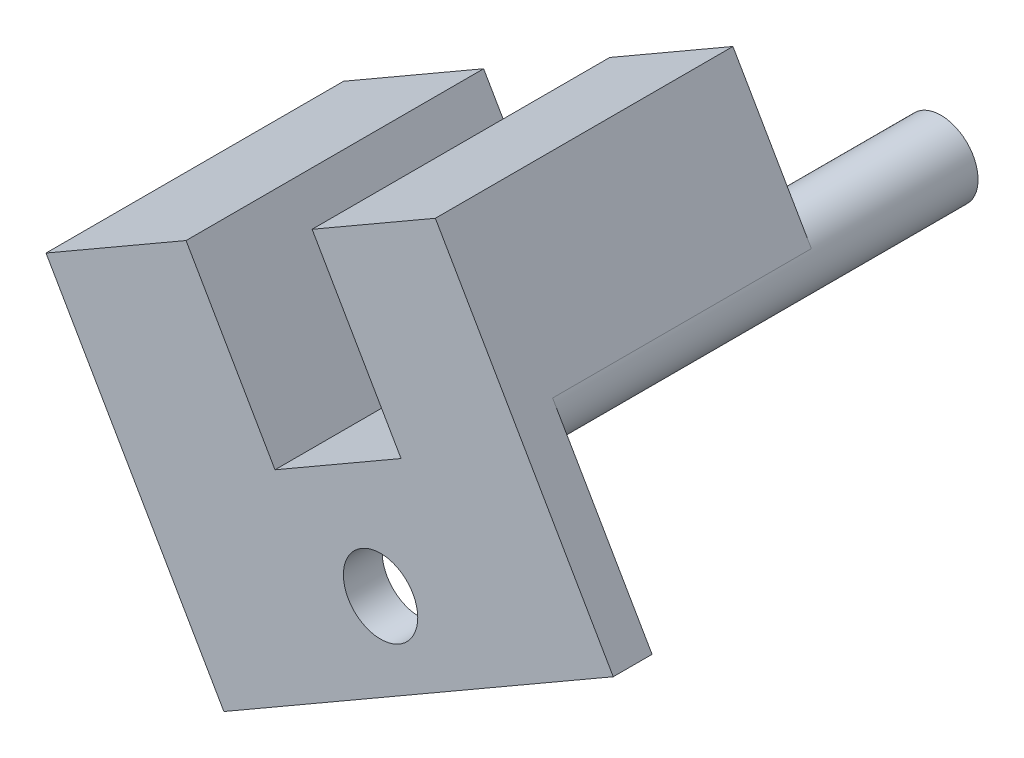
SolidWorks part; units mm, degrees
material "ABS"
ref_plane "Plan de face" through (0, 0, 0) normal (0, 0, 1) x (1, 0, 0)
ref_plane "Plan de dessus" through (0, 0, 0) normal (0, 1, 0) x (1, 0, 0)
ref_plane "Plan de droite" through (0, 0, 0) normal (1, 0, 0) x (0, 0, -1)
sketch "Esquisse1" plane through (0, 0, 0) normal (0, 0, 1) x (1, 0, 0)
  line L0 (-14.7601, -47.6561) -> (-4.7142, -41.8561)
  line L1 (-4.2932, -40.2851) -> (-6.7182, -36.0849)
  line L2 (-6.7182, -36.0849) -> (-10.5288, -38.2849)
  line L3 (-10.5288, -38.2849) -> (-7.7788, -43.0481)
  line L4 (-7.7788, -43.0481) -> (-11.6759, -45.2981)
  line L5 (-11.6759, -45.2981) -> (-14.4259, -40.5349)
  line L6 (-14.4259, -40.5349) -> (-18.756, -43.0349)
  line L7 (-18.756, -43.0349) -> (-16.331, -47.2351)
  circle A0 centre (-5.2892, -40.8601) radius 1.15 construction
  circle A1 centre (-15.3351, -46.6601) radius 1.15 construction
  arc A2 (-4.7142, -41.8561) -> (-4.2932, -40.2851) centre (-5.2892, -40.8601) ccw
  arc A3 (-16.331, -47.2351) -> (-14.7601, -47.6561) centre (-15.3351, -46.6601) ccw
  dimension "D1" = 4.5
  dimension "D2" = 5
  dimension "D3" = 6
  dimension "D4" = 0.5
extrude "Extrusion1" add sketch "Esquisse1" along normal blind 8
sketch "Esquisse2" plane through (0, 0, 8) normal (0, 0, 1) x (1, 0, 0)
  line L0 (-18.756, -43.0349) -> (-16.331, -47.2351) construction
  line L1 (-7.7788, -43.0481) -> (-11.6759, -45.2981) construction
  line L2 (-14.4259, -40.5349) -> (-18.756, -43.0349) construction
  line L3 (-11.6759, -45.2981) -> (-14.4259, -40.5349) construction
  line L4 (-4.2932, -40.2851) -> (-6.7182, -36.0849) construction
  line L5 (-10.5288, -38.2849) -> (-7.7788, -43.0481) construction
  line L6 (-6.7182, -36.0849) -> (-10.5288, -38.2849) construction
  line L7 (-18.756, -43.0349) -> (-16.331, -47.2351)
  line L8 (-7.7788, -43.0481) -> (-11.6759, -45.2981)
  line L9 (-14.4259, -40.5349) -> (-18.756, -43.0349)
  line L10 (-11.6759, -45.2981) -> (-14.4259, -40.5349)
  line L11 (-4.2932, -40.2851) -> (-6.7182, -36.0849)
  line L12 (-10.5288, -38.2849) -> (-7.7788, -43.0481)
  line L13 (-6.7182, -36.0849) -> (-10.5288, -38.2849)
  line L14 (-16.331, -47.2351) -> (-13.256, -52.5612)
  line L15 (-13.256, -52.5612) -> (-1.2182, -45.6112)
  line L16 (-1.2182, -45.6112) -> (-4.2932, -40.2851)
  circle A0 centre (-8.4121, -47.051) radius 1.15 construction
  circle A1 centre (-8.4121, -47.051) radius 1.15
  dimension "D1" = 5.5
extrude "Extrusion2" add sketch "Esquisse2" along normal blind 1.2
sketch "Esquisse3" plane through (0, 0, 0) normal (0, 0, -1) x (-1, 0, 0)
  circle A0 centre (5.2892, -40.8601) radius 1.15
  circle A1 centre (5.2892, -40.8601) radius 1.15
  arc A2 (4.2932, -40.2851) -> (4.7142, -41.8561) centre (5.2892, -40.8601) ccw construction
  circle A3 centre (15.3351, -46.6601) radius 1.15
  arc A4 (14.7601, -47.6561) -> (16.331, -47.2351) centre (15.3351, -46.6601) ccw construction
  arc M4 (14.7601, -47.6561) -> (16.331, -47.2351) centre (15.3351, -46.6601) ccw
  arc M12 (4.2932, -40.2851) -> (4.7142, -41.8561) centre (5.2892, -40.8601) ccw
extrude "Extrusion3" add sketch "Esquisse3" along normal blind 5 contours A0 M12 | A3 M4
